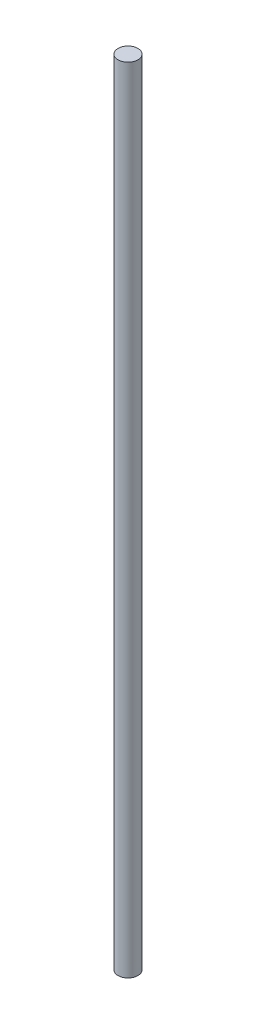
SolidWorks part; units mm, degrees
ref_plane "Front Plane" through (0, 0, 0) normal (0, 0, 1) x (1, 0, 0)
ref_plane "Top Plane" through (0, 0, 0) normal (0, 1, 0) x (1, 0, 0)
ref_plane "Right Plane" through (0, 0, 0) normal (1, 0, 0) x (0, 0, -1)
sketch "Sketch1" plane through (0, 0, 0) normal (0, 1, 0) x (1, 0, 0)
  circle A0 centre (0, 0) radius 4.7625
  dimension "D1" = 9.525
extrude "Boss-Extrude1" add sketch "Sketch1" along normal blind 380
